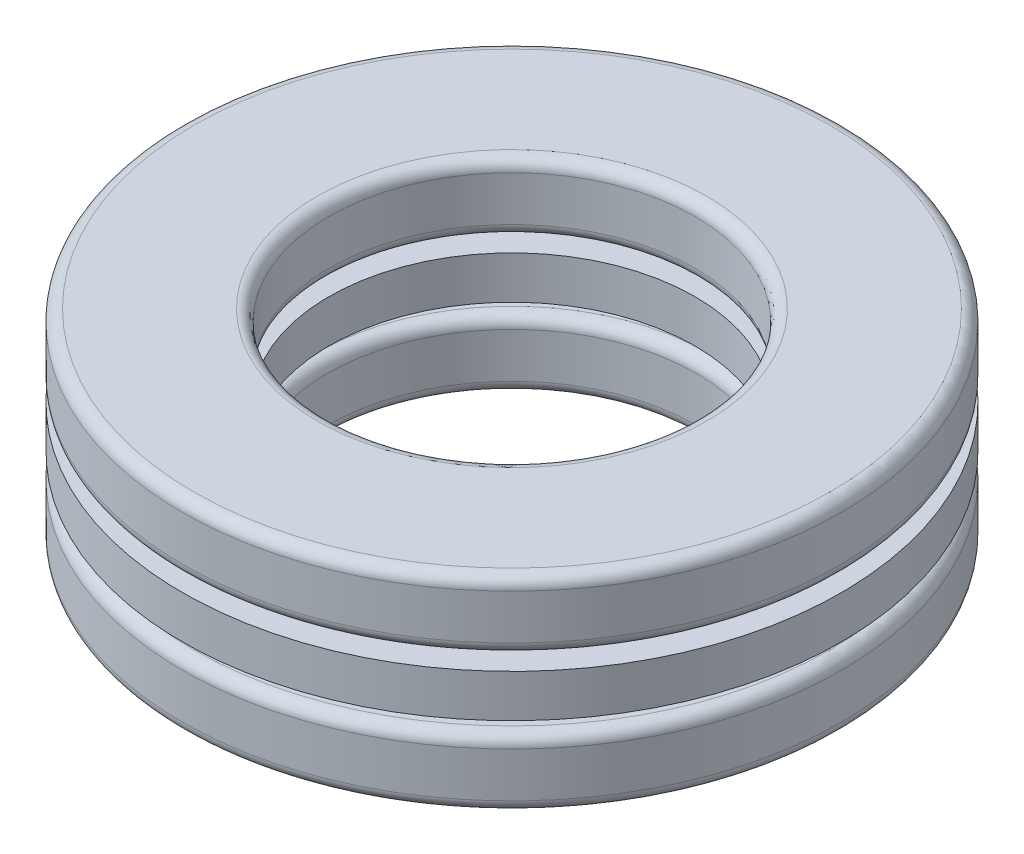
SolidWorks part; units mm, degrees
ref_plane "Front Plane" through (0, 0, 0) normal (0, 0, 1) x (1, 0, 0)
ref_plane "Top Plane" through (0, 0, 0) normal (0, 1, 0) x (1, 0, 0)
ref_plane "Right Plane" through (0, 0, 0) normal (1, 0, 0) x (0, 0, -1)
sketch "Sketch1" plane through (0, 0, 0) normal (1, 0, 0) x (0, 0, -1)
  line L0 (-22.5, 0) -> (22.5, 0) construction
  line L1 (0, -7) -> (0, 7) construction
  line L2 (-22.5, 1.4583) -> (-12.5, 1.4583)
  line L3 (-22.5, 1.4583) -> (-22.5, -1.4583)
  line L4 (-22.5, -1.4583) -> (-12.5, -1.4583)
  line L5 (-12.5, 1.4583) -> (-12.5, -1.4583)
  line L6 (-17.5, 2.3333) -> (-17.5, -2.3333) construction
  line L7 (-17.5, 2.3333) -> (-17.5, 7) construction
  circle A0 centre (-17.5, 0) radius 2.3333 construction
  point P13 (-17.5, 1.4583)
  dimension "D1" = 4.6667
  dimension "OD" = 45
  dimension "Shaft Dia" = 25
  dimension "Th" = 14
  dimension "D2" = 2.9167
  dimension "D3" = 4.6667
revolve "Revolve1" add sketch "Sketch1" angle 360 about L1
sketch "Sketch3" plane through (0, 0, 0) normal (1, 0, 0) x (0, 0, -1)
  line L0 (-17.5, 2.3333) -> (-17.5, -2.3333)
  arc A0 (-17.5, 2.3333) -> (-17.5, -2.3333) centre (-17.5, 0) ccw
  circle A1 centre (-17.5, 0) radius 2.3333 construction
revolve "Cut-Revolve1" cut sketch "Sketch3" angle 360 about L0
sketch "Sketch2" plane through (0, 0, 0) normal (1, 0, 0) x (0, 0, -1)
  line L0 (-17.5, 2.3333) -> (-17.5, -2.3333)
  arc A0 (-17.5, 2.3333) -> (-17.5, -2.3333) centre (-17.5, 0) ccw
  circle A2 centre (-17.5, 0) radius 2.3333 construction
revolve "Revolve2" add sketch "Sketch2" angle 360 about L0
ref_axis "Axis1" through (0, 7, 0) along (0, -1, 0)
pattern_circular "CirPattern1" count 17 every 21.176 about axis through (0, 7, 0) along (0, -1, 0) of bodies 187
pattern_circular "CirPattern2" count 17 every 21.176 about axis through (0, 0, 0) along (0, 1, 0) of "Cut-Revolve1"
sketch "Sketch4" plane through (0, 0, 0) normal (1, 0, 0) x (0, 0, -1)
  line L0 (-22.5, 1.4583) -> (-22.5, -1.4583) construction
  line L2 (-22.5, 7) -> (-22.5, -7) construction
  line L3 (-21.7, 7) -> (-13.3, 7)
  line L4 (-12.5, 3.1333) -> (-12.5, 6.2)
  line L5 (-21.7, -7) -> (-13.4, -7)
  line L6 (-22.5, -6.2) -> (-22.5, -3.1333)
  line L8 (-21.7, 2.3333) -> (-13.3, 2.3333)
  line L10 (-12.5, 1.4583) -> (-12.5, -1.4583) construction
  line L11 (0, 0) -> (-22.5, 0) construction
  line L12 (-22.5, 0) -> (22.5, 0) construction
  line L13 (0, 0) -> (0, 7) construction
  line L14 (-22.5, 6.2) -> (-22.5, 3.1333)
  line L15 (-12.6, -3.1333) -> (-12.6, -6.2)
  line L16 (-21.7, -2.3333) -> (-13.4, -2.3333)
  arc A0 (-21.7, 7) -> (-22.5, 6.2) centre (-21.7, 6.2) ccw
  arc A1 (-13.3, 7) -> (-12.5, 6.2) centre (-13.3, 6.2) cw
  arc A2 (-13.3, 2.3333) -> (-12.5, 3.1333) centre (-13.3, 3.1333) ccw
  arc A3 (-13.4, -2.3333) -> (-12.6, -3.1333) centre (-13.4, -3.1333) cw
  arc A4 (-22.5, -3.1333) -> (-21.7, -2.3333) centre (-21.7, -3.1333) cw
  arc A5 (-21.7, -7) -> (-22.5, -6.2) centre (-21.7, -6.2) cw
  arc A6 (-21.7, 2.3333) -> (-22.5, 3.1333) centre (-21.7, 3.1333) cw
  arc A7 (-13.4, -7) -> (-12.6, -6.2) centre (-13.4, -6.2) ccw
  point P25 (-22.5, -2.3333)
  point P26 (-8.5, 0.0333)
  point P29 (-8.5, -0.0333)
  dimension "r" = 0.8
  dimension "D5" = 45
  dimension "D1" = 4.6667
  dimension "Ht" = 14
  dimension "D3" = 25
  dimension "dia2" = 25.2
  dimension "dia1" = 45
revolve "Revolve3" add sketch "Sketch4" angle 360 about L1
equation "\"D1@Sketch1\" = \"Th@Sketch1\"/3"
equation "\"D2@Sketch1\" = \"D1@Sketch1\"*.625"
equation "\"Balls@CirPattern1\" = \"OD@Sketch1\"*.375"
equation "\"Angle@CirPattern1\" = 360/\"Balls@CirPattern1\""
equation "\"D1@CirPattern2\" = \"Balls@CirPattern1\""
equation "\"D2@CirPattern2\" = \"Angle@CirPattern1\""
equation "\"D1@Sketch4\" = \"D3@Sketch1\""
